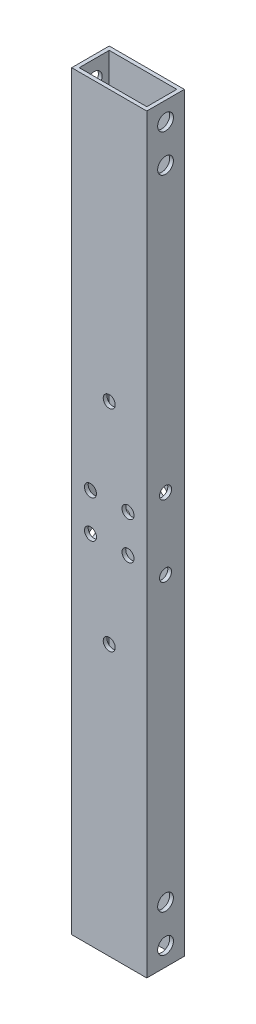
SolidWorks part; units mm, degrees
ref_plane "前视基准面" through (0, 0, 0) normal (0, 0, 1) x (1, 0, 0)
ref_plane "上视基准面" through (0, 0, 0) normal (0, 1, 0) x (1, 0, 0)
ref_plane "右视基准面" through (0, 0, 0) normal (1, 0, 0) x (0, 0, -1)
other "Configuration Table"
sketch "草图1" plane through (0, 0, 0) normal (0, 1, 0) x (1, 0, 0)
  line L1 (-10, -5) -> (10, -5)
  line L2 (-10, -5) -> (-10, 5)
  line L3 (-10, 5) -> (10, 5)
  line L4 (10, -5) -> (10, 5)
  line L5 (-10, -5) -> (10, 5) construction
  line L6 (-10, 5) -> (10, -5) construction
  point P0 (0, 0)
  dimension "D1" = 20
  dimension "D2" = 10
extrude "拉伸-薄壁1" add sketch "草图1" along normal blind 200 thin thin type one direction reverse wall 1
sketch "草图2" plane through (10, 0, 0) normal (1, 0, 0) x (0, 0, -1)
  line L0 (5, 200) -> (5, 0) construction
  line L1 (-5, 200) -> (5, 200)
  line L2 (-5, 200) -> (-5, 180)
  line L3 (-5, 180) -> (5, 180)
  line L4 (5, 200) -> (5, 180)
  line L6 (-5, 0) -> (5, 0)
  line L7 (-5, 0) -> (-5, 20)
  line L8 (-5, 20) -> (5, 20)
  line L9 (5, 0) -> (5, 20)
  dimension "D1" = 20
  dimension "D2" = 20
sketch "草图3" plane through (0, 0, 5) normal (0, 0, 1) x (1, 0, 0)
  line L0 (-10, 100) -> (10, 100) construction
  line L1 (-10, 200) -> (-10, 0) construction
  line L2 (10, 200) -> (10, 0) construction
  line L3 (0, 375) -> (0, 380.2879) construction
  circle A0 centre (0, 128) radius 1.6
  circle A1 centre (0, 72) radius 1.6
  dimension "D2" = 3.2
  dimension "D1" = 28
extrude "切除-拉伸1" cut sketch "草图3" against normal through all
sketch "草图4" plane through (10, 0, 0) normal (1, 0, 0) x (0, 0, -1)
  line L0 (-5, 100) -> (5, 100) construction
  line L1 (-5, 200) -> (-5, 0) construction
  line L2 (5, 200) -> (5, 0) construction
  circle A0 centre (0, 109.5) radius 1.6
  circle A1 centre (0, 90.5) radius 1.6
  dimension "D1" = 3.2
  dimension "D2" = 5
  dimension "D3" = 9.5
extrude "切除-拉伸2" cut sketch "草图4" against normal through all
sketch "草图5" plane through (0, 0, -5) normal (0, 0, -1) x (-1, 0, 0)
  line L0 (-10, 100) -> (10, 100) construction
  line L1 (-10, 200) -> (-10, 0) construction
  line L2 (10, 200) -> (10, 0) construction
  line L3 (0, 100) -> (0, 158.9772) construction
  circle A0 centre (-5, 105) radius 1.6
  circle A1 centre (-5, 95) radius 1.6
  circle A2 centre (5, 95) radius 1.6
  circle A3 centre (5, 105) radius 1.6
  dimension "D1" = 3.2
  dimension "D2" = 5
  dimension "D3" = 5
extrude "切除-拉伸3" cut sketch "草图5" against normal through all
sketch "草图6" plane through (10, 0, 0) normal (1, 0, 0) x (0, 0, -1)
  line L0 (-5, 10) -> (5, 10) construction
  line L1 (-5, 0) -> (-5, 20) construction
  line L2 (5, 0) -> (5, 20) construction
  line L3 (0, 20) -> (0, 0) construction
  line L4 (-5, 20) -> (5, 20) construction
  line L6 (5, 100) -> (-5, 100) construction
  line L7 (5, 200) -> (5, 0) construction
  line L8 (-5, 200) -> (-5, 0) construction
  line L9 (0, 180) -> (0, 200) construction
  line L10 (-5, 190) -> (5, 190) construction
  circle A0 centre (0, 5) radius 2.1
  circle A1 centre (0, 15) radius 2.1
  circle A2 centre (0, 185) radius 2.1
  circle A3 centre (0, 195) radius 2.1
  dimension "D1" = 4.2
  dimension "D2" = 5
extrude "切除-拉伸4" cut sketch "草图6" against normal through all
